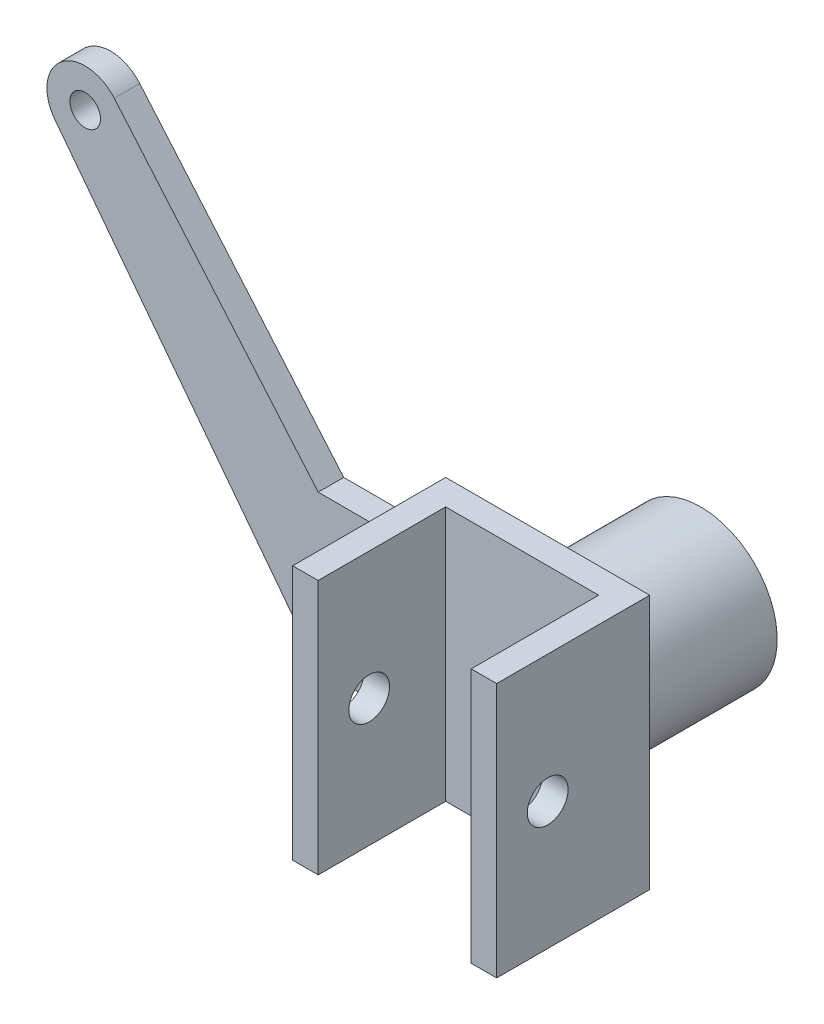
SolidWorks part; units mm, degrees
ref_plane "Front Plane" through (0, 0, 0) normal (0, 0, 1) x (1, 0, 0)
ref_plane "Top Plane" through (0, 0, 0) normal (0, 1, 0) x (1, 0, 0)
ref_plane "Right Plane" through (0, 0, 0) normal (1, 0, 0) x (0, 0, -1)
sketch "Sketch1" plane through (0, 0, 0) normal (0, 0, 1) x (1, 0, 0)
  line L1 (-20, -25) -> (20, -25)
  line L2 (-20, -25) -> (-20, 25)
  line L3 (-20, 25) -> (20, 25)
  line L4 (20, -25) -> (20, 25)
  line L5 (-20, -25) -> (20, 25) construction
  line L6 (-20, 25) -> (20, -25) construction
  point P0 (0, 0)
  dimension "D1" = 40
  dimension "D2" = 50
extrude "Boss-Extrude1" add sketch "Sketch1" along normal blind 5
sketch "Sketch2" plane through (0, 0, 5) normal (0, 0, 1) x (1, 0, 0)
  line L0 (-20, -25) -> (20, -25) construction
  line L1 (-20, 25) -> (-15, 25)
  line L2 (-20, 25) -> (-20, -25)
  line L3 (-20, -25) -> (-15, -25)
  line L4 (-15, 25) -> (-15, -25)
  line L6 (20, 25) -> (15, 25)
  line L7 (20, 25) -> (20, -25)
  line L8 (20, -25) -> (15, -25)
  line L9 (15, 25) -> (15, -25)
  dimension "D1" = 5
  dimension "D2" = 5
extrude "Boss-Extrude2" add sketch "Sketch2" along normal blind 25
sketch "Sketch3" plane through (-20, 0, 0) normal (-1, 0, 0) x (0, 0, 1)
  line L0 (15, 25) -> (15, -25) construction
  line L1 (30, 25) -> (0, 25) construction
  line L2 (30, -25) -> (0, -25) construction
  line L3 (0, 0) -> (30, 0) construction
  line L4 (30, 25) -> (30, -25) construction
  circle A0 centre (20, 0) radius 4
  dimension "D1" = 8
  dimension "D3" = 25
  dimension "D2" = 10
extrude "Cut-Extrude1" cut sketch "Sketch3" against normal through all
sketch "Sketch4" plane through (-20, 0, 0) normal (-1, 0, 0) x (0, 0, 1)
  line L0 (0, 0) -> (30, 0) construction
  line L2 (30, 25) -> (30, -25) construction
  line L3 (0, 25) -> (0, -25) construction
  line L4 (5, -15) -> (0, -15)
  line L5 (5, -15) -> (5, 15)
  line L6 (5, 15) -> (0, 15)
  line L7 (0, -15) -> (0, 15)
  line L8 (5, -15) -> (0, 15) construction
  line L9 (5, 15) -> (0, -15) construction
  point P4 (2.5, 0)
  dimension "D1" = 5
  dimension "D2" = 30
extrude "Boss-Extrude3" add sketch "Sketch4" along normal blind 20
ref_plane "Plane1" through (0, 0, 5) normal (0, 0, 1) x (1, 0, 0)
sketch "Sketch5" plane through (0, 0, 5) normal (0, 0, 1) x (1, 0, 0)
  line L4 (-40, 15) -> (-40, -15)
  line L5 (-79.9784, 61.8986) -> (-40, 15)
  line L6 (-91.6419, 52.4748) -> (-40, -15)
  circle A2 centre (-85.6861, 57.0331) radius 3
  circle A3 centre (-85.6861, 57.0331) radius 3 construction
  arc A4 (-79.9784, 61.8986) -> (-91.6419, 52.4748) centre (-85.6861, 57.0331) ccw
  dimension "D1" = 6
  dimension "D2" = 15
extrude "Boss-Extrude4" add sketch "Sketch5" against normal blind 5
sketch "Sketch6" plane through (0, 0, 0) normal (0, 0, -1) x (-1, 0, 0)
  circle A0 centre (0, 0) radius 15
  dimension "D1" = 30
extrude "Boss-Extrude5" add sketch "Sketch6" along normal blind 30
equation "\"rubberthickness\"= 0.0165m"
equation "\"D1@Boss-Extrude2\" = \"t_thigh\" + 0.005m"
equation "\"D2@Sketch3\" = \"t_thigh\" / 2"
equation "\"t_thigh\"= 0.0200m"
